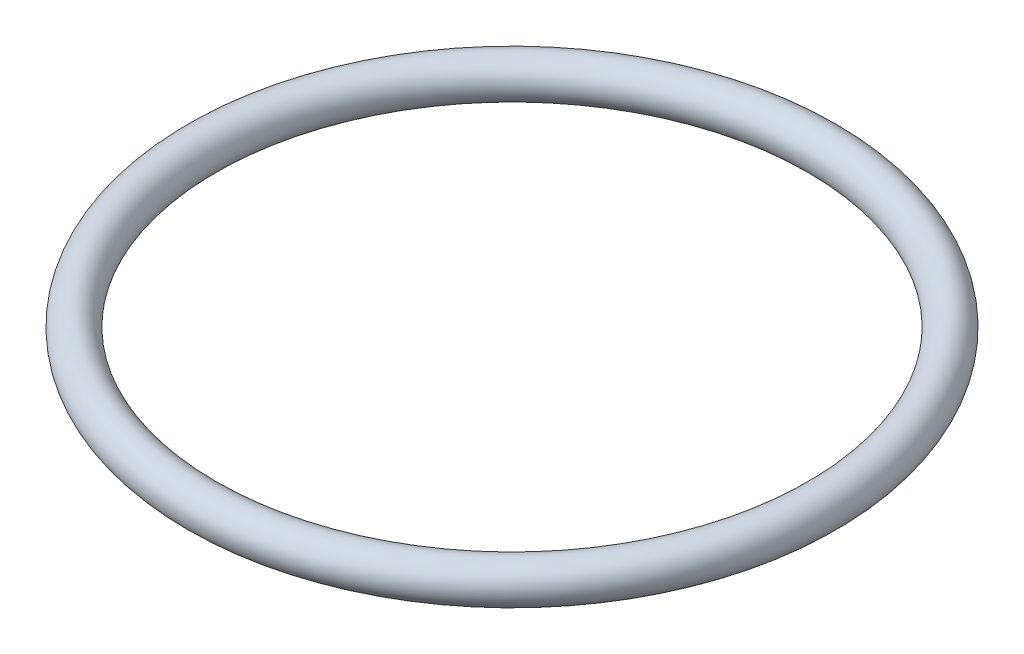
SolidWorks part; units mm, degrees
ref_plane "Front Plane" through (0, 0, 0) normal (0, 0, 1) x (1, 0, 0)
ref_plane "Top Plane" through (0, 0, 0) normal (0, 1, 0) x (1, 0, 0)
ref_plane "Right Plane" through (0, 0, 0) normal (1, 0, 0) x (0, 0, -1)
sketch "Sketch1" plane through (0, 0, 0) normal (0, 0, 1) x (1, 0, 0)
  line L0 (0, 0) -> (0, 5) construction
  circle A0 centre (-23.5, 0) radius 1.5
  dimension "D1" = 3
  dimension "D2" = 23.5
  dimension "D3" = 5
revolve "Revolve1" add sketch "Sketch1" angle 360 about L0
